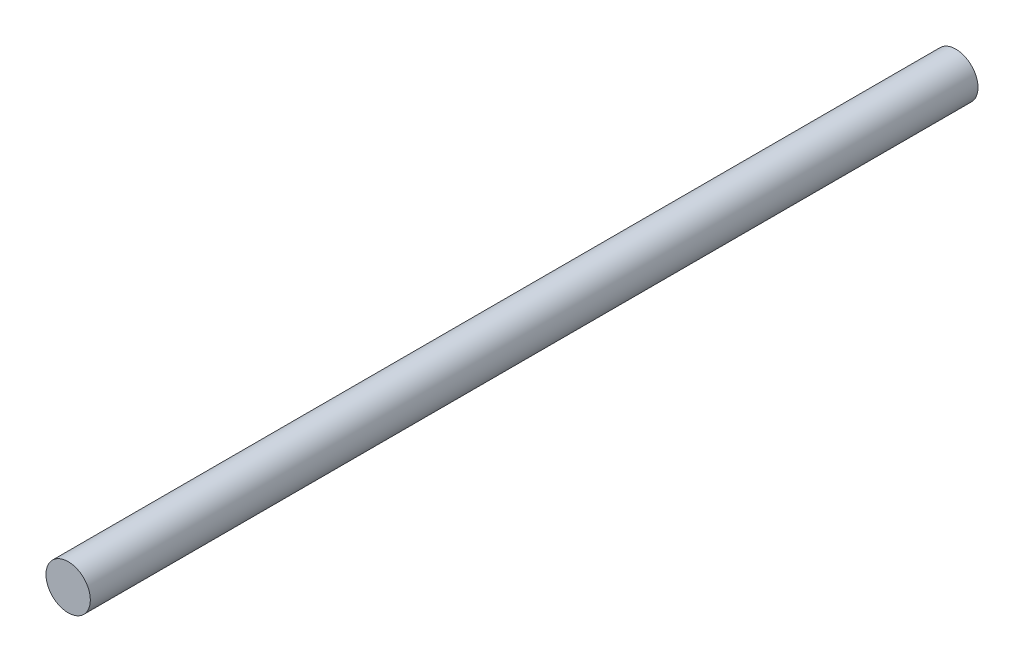
SolidWorks part; units mm, degrees
ref_plane "Спереди" through (0, 0, 0) normal (0, 0, 1) x (1, 0, 0)
ref_plane "Сверху" through (0, 0, 0) normal (0, 1, 0) x (1, 0, 0)
ref_plane "Справа" through (0, 0, 0) normal (1, 0, 0) x (0, 0, -1)
sketch "Эскиз1" plane through (0, 0, 0) normal (0, 0, 1) x (1, 0, 0)
  circle A0 centre (0, 0) radius 2
extrude "Tie_stud" add sketch "Эскиз1" along normal blind 80 from offset 33
